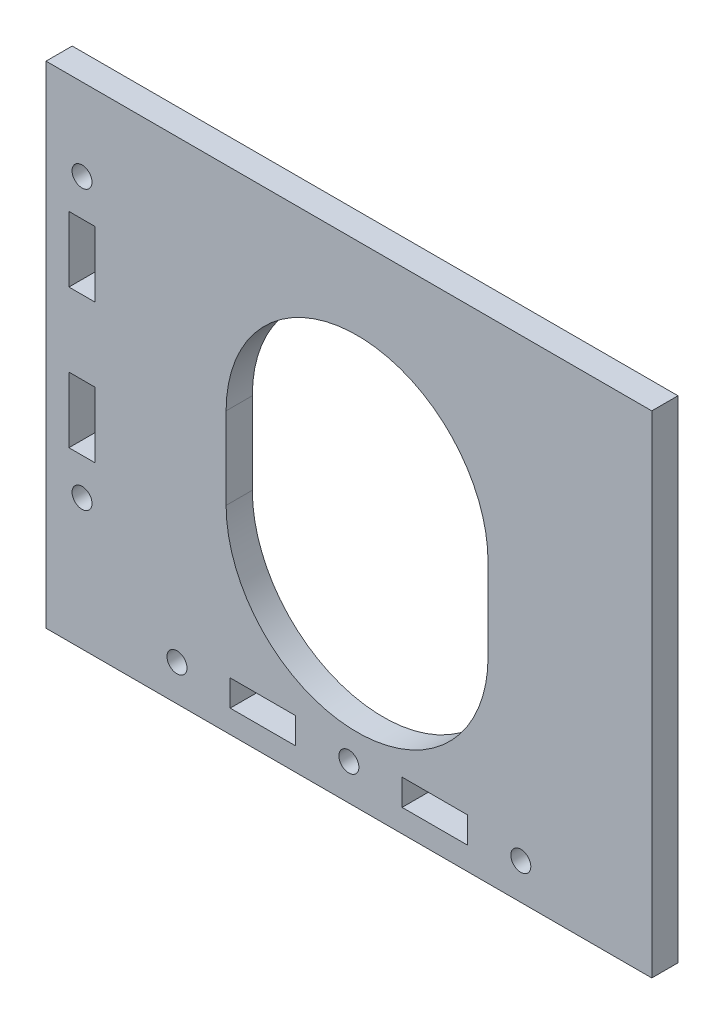
SolidWorks part; units mm, degrees
ref_plane "Front Plane" through (0, 0, 0) normal (0, 0, 1) x (1, 0, 0)
ref_plane "Top Plane" through (0, 0, 0) normal (0, 1, 0) x (1, 0, 0)
ref_plane "Right Plane" through (0, 0, 0) normal (1, 0, 0) x (0, 0, -1)
sketch "Model" plane through (0, 0, 0) normal (0, 0, 1) x (1, 0, 0)
  line L0 (41.25, 0) -> (61.25, 0)
  line L1 (41.25, -8) -> (41.25, 0)
  line L2 (113.75, -8) -> (93.75, -8)
  line L3 (113.75, 0) -> (113.75, -8)
  line L4 (93.75, 0) -> (113.75, 0)
  line L5 (93.75, -8) -> (93.75, 0)
  line L7 (170, 135) -> (-15, 135)
  line L8 (170, -15) -> (170, 135)
  line L10 (61.25, 0) -> (61.25, -8)
  line L11 (61.25, -8) -> (41.25, -8)
  line L12 (40, 45) -> (40, 70)
  line L13 (120, 70) -> (120, 45)
  line L14 (-8, 78.75) -> (-8, 98.75)
  line L15 (-8, 98.75) -> (0, 98.75)
  line L16 (0, 98.75) -> (0, 78.75)
  line L17 (0, 78.75) -> (-8, 78.75)
  line L18 (-8, 36.25) -> (-8, 56.25)
  line L19 (-8, 56.25) -> (0, 56.25)
  line L20 (0, 56.25) -> (0, 36.25)
  line L21 (0, 36.25) -> (-8, 36.25)
  line L22 (-15, -15) -> (-15, 135)
  line L24 (170, -15) -> (-15, -15)
  arc A4 (120, 70) -> (40, 70) centre (80, 70) ccw
  arc A5 (40, 45) -> (120, 45) centre (80, 45) ccw
  circle A6 centre (77.5, -4) radius 3.05
  circle A7 centre (-4, 110) radius 3.05
  circle A8 centre (-4, 25) radius 3.05
  circle A9 centre (25, -4) radius 3.05
  circle A10 centre (130, -4) radius 3.05
extrude "Boss-Extrude1" add sketch "Model" along normal blind 8
